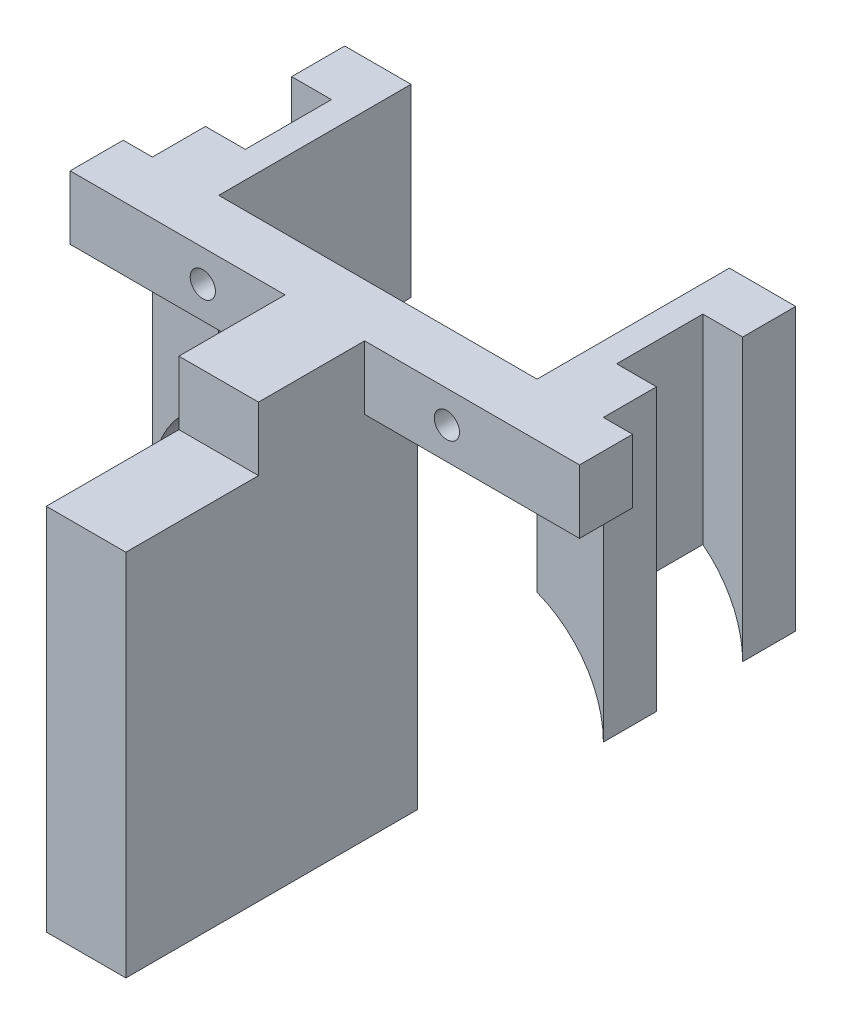
SolidWorks part; units mm, degrees
ref_plane "前视基准面" through (0, 0, 0) normal (0, 0, 1) x (1, 0, 0)
ref_plane "上视基准面" through (0, 0, 0) normal (0, 1, 0) x (1, 0, 0)
ref_plane "右视基准面" through (0, 0, 0) normal (1, 0, 0) x (0, 0, -1)
other "Configuration Table"
sketch "草图1" plane through (0, 0, 0) normal (0, 0, 1) x (1, 0, 0)
  line L0 (18.5882, -2.4) -> (-49981.4118, -2.4) construction
  line L1 (0, 0) -> (38.4, 0)
  line L2 (0, 0) -> (0, -4.8)
  line L3 (0, -4.8) -> (38.4, -4.8)
  line L4 (38.4, 0) -> (38.4, -4.8)
  circle A0 centre (10, -2.4) radius 0.95
  circle A1 centre (28.4, -2.4) radius 0.95
  point P9 (0, -2.4)
  dimension "D4" = 1.9
  dimension "D5" = 1.9
  dimension "D1" = 38.4
  dimension "D2" = 4.8
  dimension "D3" = 10
  dimension "D6" = 10
extrude "凸台-拉伸1" add sketch "草图1" along normal blind 4
sketch "草图4" plane through (0, 0, 0) normal (0, 1, 0) x (1, 0, 0)
  line L0 (2.2, 0) -> (2.2, 4)
  line L1 (38.4, 0) -> (0, 0) construction
  line L2 (2.2, 4) -> (5.2, 4)
  line L3 (5.2, 4) -> (5.2, 10.5)
  line L4 (5.2, 10.5) -> (2.2, 10.5)
  line L5 (2.2, 10.5) -> (2.2, 14.5)
  line L6 (2.2, 14.5) -> (7.2, 14.5)
  line L7 (7.2, 14.5) -> (7.2, 0)
  line L8 (7.2, 0) -> (2.2, 0)
  line L10 (0, -4) -> (0, 0) construction
  line L11 (36.2, 0) -> (31.2, 0)
  line L12 (31.2, 0) -> (31.2, 14.5)
  line L13 (31.2, 14.5) -> (36.2, 14.5)
  line L14 (36.2, 14.5) -> (36.2, 10.5)
  line L15 (36.2, 10.5) -> (33.2, 10.5)
  line L16 (33.2, 10.5) -> (33.2, 4)
  line L17 (33.2, 4) -> (36.2, 4)
  line L18 (36.2, 4) -> (36.2, 0)
  line L19 (38.4, -4) -> (38.4, 0) construction
  dimension "D1" = 2.2
  dimension "D2" = 4
  dimension "D3" = 6.5
  dimension "D4" = 4
  dimension "D5" = 3
  dimension "D6" = 2
  dimension "D7" = 2
  dimension "D8" = 4
  dimension "D9" = 6.5
  dimension "D10" = 4
  dimension "D11" = 3
  dimension "D12" = 2.2
extrude "凸台-拉伸2" add sketch "草图4" against normal blind 21.2
sketch "草图5" plane through (0, 0, -14.5) normal (0, 0, -1) x (-1, 0, 0)
  line L0 (-10, -2.4) -> (-10, 49997.6) construction
  line L1 (-6.4961, -21.2) -> (-50006.4961, -21.2) construction
  line L3 (-7.2, -21.2) -> (-2.2, -21.2) construction
  line L4 (-2.2, -21.2) -> (-2.2, 0) construction
  line L5 (-28.4, -2.4) -> (-28.4, -50002.4) construction
  line L6 (-36.2, -21.2) -> (-36.2, 0) construction
  circle A0 centre (-10, -21.2) radius 7.8
  circle A1 centre (-28.4, -21.2) radius 7.8
extrude "切除-拉伸2" cut sketch "草图5" against normal blind 14.5
sketch "草图8" plane through (0, 0, 4) normal (0, 0, 1) x (1, 0, 0)
  line L0 (19.2, -4.8) -> (19.2, 49995.2) construction
  line L1 (0, -4.8) -> (38.4, -4.8) construction
  line L2 (38.4, -2.4) -> (-49961.6, -2.4) construction
  line L3 (38.4, -4.8) -> (38.4, 0) construction
  line L5 (16.2, 0) -> (22.2, 0)
  line L6 (16.2, 0) -> (16.2, -4.8)
  line L7 (16.2, -4.8) -> (22.2, -4.8)
  line L8 (22.2, 0) -> (22.2, -4.8)
  line L9 (16.2, 0) -> (22.2, -4.8) construction
  line L10 (16.2, -4.8) -> (22.2, 0) construction
  point P4 (19.2, -4.8)
  point P9 (38.4, -2.4)
  point P10 (19.2, -2.4)
  dimension "D1" = 6
extrude "凸台-拉伸4" add sketch "草图8" along normal blind 8
sketch "草图9" plane through (0, -4.8, 0) normal (0, -1, 0) x (1, 0, 0)
  line L0 (7.2, 0) -> (31.2, 0) construction
  line L1 (16.2, 0) -> (22.2, 0)
  line L2 (16.2, 0) -> (16.2, 22)
  line L3 (16.2, 22) -> (22.2, 22)
  line L4 (22.2, 0) -> (22.2, 22)
  line L5 (16.2, 12) -> (22.2, 12) construction
  line L6 (16.2, 12) -> (16.2, 4) construction
  line L7 (22.2, 12) -> (22.2, 4) construction
  dimension "D1" = 10
extrude "凸台-拉伸5" add sketch "草图9" along normal blind 27.8
